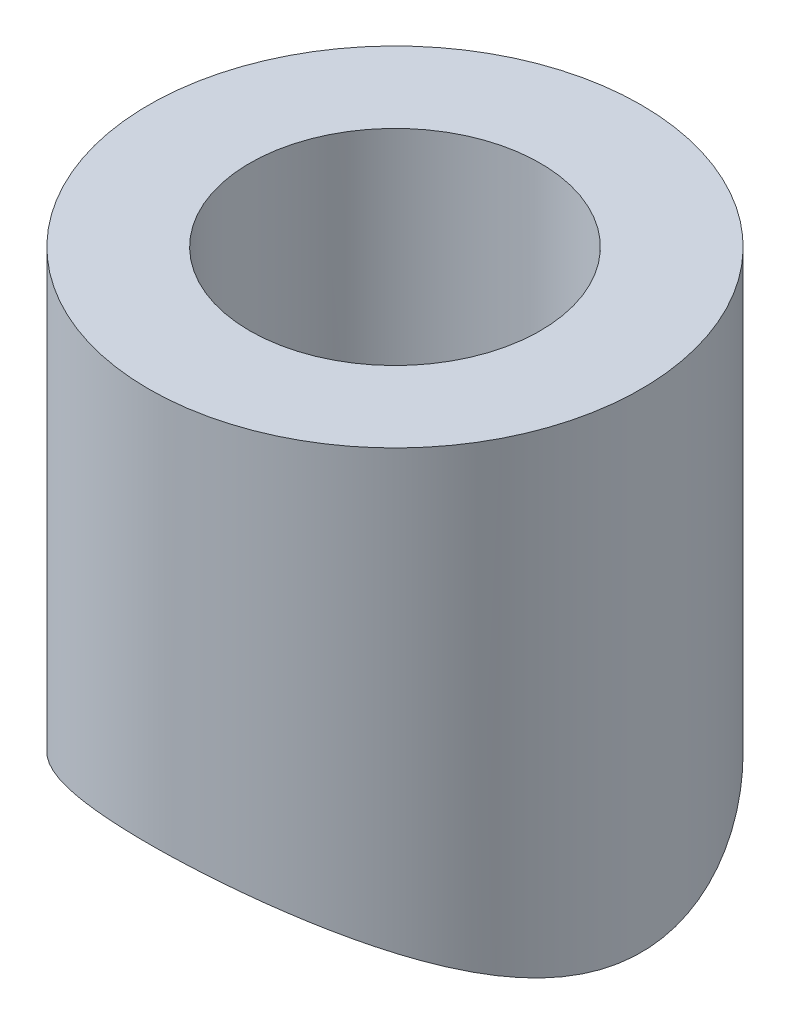
SolidWorks part; units mm, degrees
ref_plane "Front Plane" through (0, 0, 0) normal (0, 0, 1) x (1, 0, 0)
ref_plane "Top Plane" through (0, 0, 0) normal (0, 1, 0) x (1, 0, 0)
ref_plane "Right Plane" through (0, 0, 0) normal (1, 0, 0) x (0, 0, -1)
sketch "Sketch1" plane through (0, 0, 0) normal (0, 1, 0) x (1, 0, 0)
  circle A0 centre (0, 0) radius 10
  point P4 (0, 0)
  dimension "D1" = 20
extrude "Boss-Extrude1" add sketch "Sketch1" along normal blind 20
sketch "Sketch2" plane through (0, 0, 0) normal (0, 0, 1) x (1, 0, 0)
  circle A0 centre (0, -11) radius 15
  point P2 (0, 0)
  dimension "D1" = 30
  dimension "D2" = 11
extrude "Cut-Extrude1" cut sketch "Sketch2" along normal through all both and the other way through all
hole_wizard "G1/4 Tapped Hole1" positions "Sketch3" profile "Sketch4" tap size "G1/4" standard "ISO" end condition through all
sketch "Sketch3" plane through (0, 20, 0) normal (0, 1, 0) x (1, 0, 0)
  point P0 (0, 0)
sketch "Sketch4" plane through (0, 20, 0) normal (1, 0, 0) x (0, 0, 1)
  line L0 (0, 0) -> (0, 20.58)
  line L1 (0, 20.58) -> (5.9, 20.58)
  line L2 (5.9, 20.58) -> (5.9, 0)
  line L5 (5.9, 0) -> (0, 0)
  line L11 (0, -6.35) -> (0, 107.95) construction
  dimension "Thru Tap Drill Dia." = 11.8
  dimension "Thru Tap Drill Depth" = 20.58
cosmetic thread "Hole Thread1"
